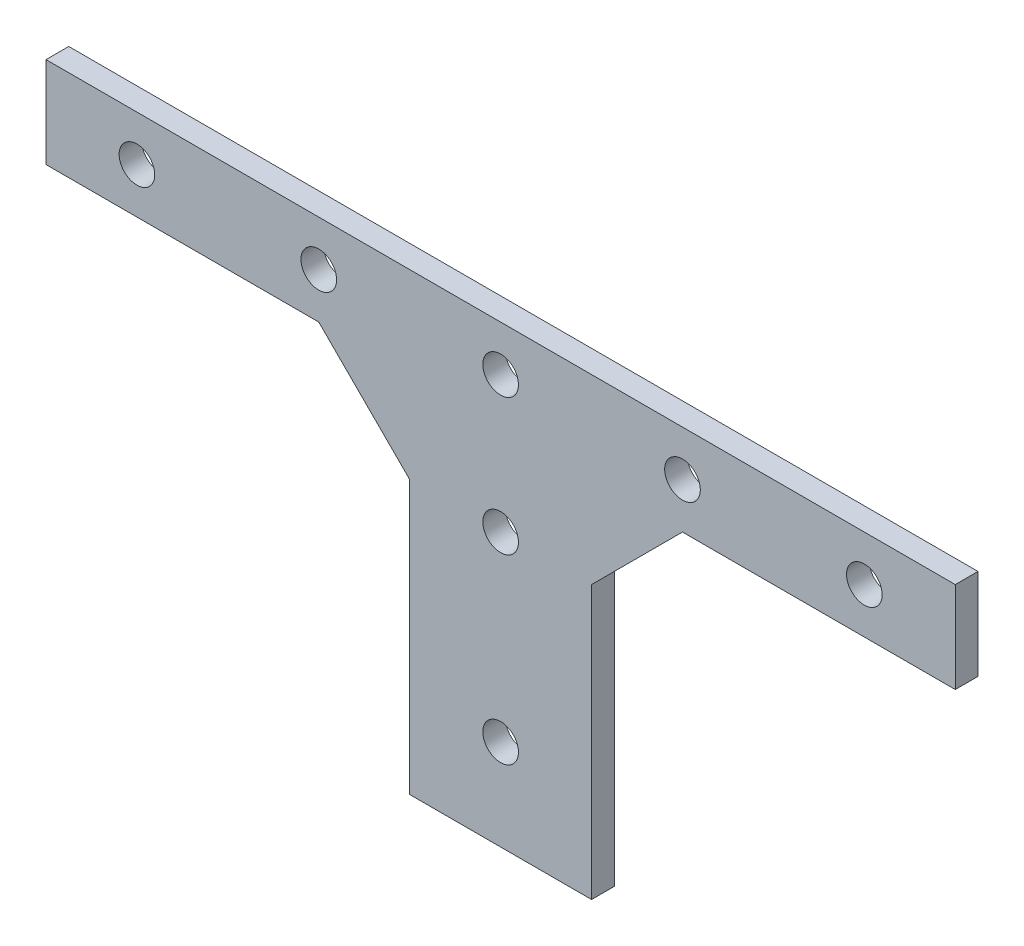
SolidWorks part; units mm, degrees
ref_plane "Front Plane" through (0, 0, 0) normal (0, 0, 1) x (1, 0, 0)
ref_plane "Top Plane" through (0, 0, 0) normal (0, 1, 0) x (1, 0, 0)
ref_plane "Right Plane" through (0, 0, 0) normal (1, 0, 0) x (0, 0, -1)
sketch "Sketch1" plane through (0, 0, 0) normal (0, 0, 1) x (1, 0, 0)
  line L0 (41.275, -25.4) -> (41.275, -63.5)
  line L2 (41.275, -63.5) -> (66.675, -63.5)
  line L4 (66.675, -63.5) -> (66.675, -25.4)
  line L5 (79.375, -12.7) -> (117.475, -12.7)
  line L7 (117.475, -12.7) -> (117.475, 0)
  line L9 (117.475, 0) -> (-9.525, 0)
  line L10 (-9.525, 0) -> (-9.525, -12.7)
  line L11 (-9.525, -12.7) -> (28.575, -12.7)
  line L13 (66.675, -25.4) -> (79.375, -12.7)
  line L14 (53.975, -12.7) -> (53.975, -25.4) construction
  line L15 (41.275, -25.4) -> (28.575, -12.7)
  line L16 (53.975, -63.5) -> (53.975, 0) construction
  line L17 (117.475, -6.35) -> (-9.525, -6.35) construction
  line L18 (117.475, -6.35) -> (104.775, -6.35) construction
  line L19 (104.775, -6.35) -> (79.375, -6.35) construction
  line L20 (79.375, -6.35) -> (53.975, -6.35) construction
  line L21 (53.975, -6.35) -> (28.575, -6.35) construction
  line L22 (28.575, -6.35) -> (3.175, -6.35) construction
  line L23 (53.975, -25.4) -> (53.975, -50.8) construction
  point P10 (0, 0)
  dimension "D3" = 127
extrude "Boss-Extrude1" add sketch "Sketch1" along normal blind 3.175
hole_wizard "#10 Clearance Hole1" positions "Sketch4" profile "Sketch5" hole size "#10" standard "ANSI Inch" end condition through all
sketch "Sketch4" plane through (0, 0, 3.175) normal (0, 0, 1) x (1, 0, 0)
  point P0 (3.175, -6.35)
  point P3 (28.575, -6.35)
  point P6 (53.975, -6.35)
  point P13 (104.775, -6.35)
  point P16 (53.975, -25.4)
  point P19 (53.975, -50.8)
  point P22 (79.375, -6.35)
  point P26 (0, 0)
sketch "Sketch5" plane through (3.175, -6.35, 3.175) normal (1, 0, 0) x (0, -1, 0)
  line L0 (0, 0) -> (0, 3.175)
  line L1 (0, 3.175) -> (2.4892, 3.175)
  line L2 (2.4892, 3.175) -> (2.4892, 0)
  line L5 (2.4892, 0) -> (0, 0)
  line L11 (0, -6.35) -> (0, 107.95) construction
  dimension "Thru Hole Dia." = 4.9784
  dimension "Thru Hole Depth" = 3.175
